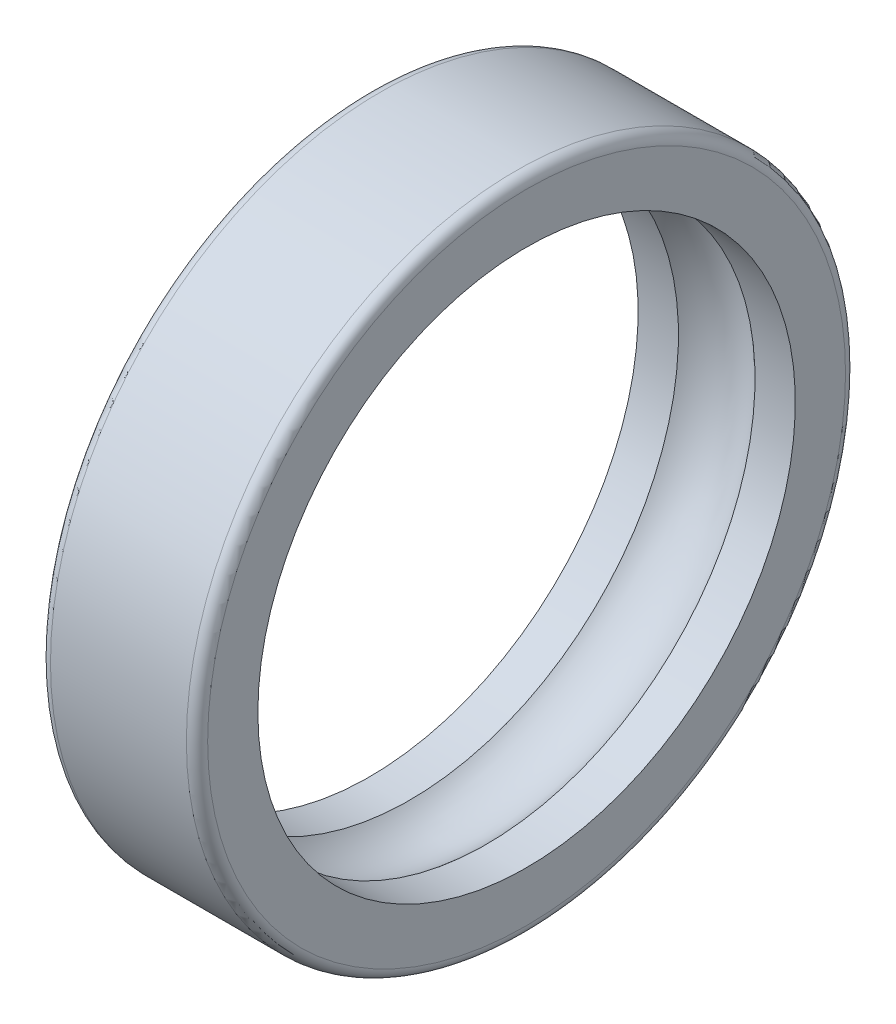
SolidWorks part; units mm, degrees
ref_plane "Front Plane" through (0, 0, 0) normal (0, 0, 1) x (1, 0, 0)
ref_plane "Top Plane" through (0, 0, 0) normal (0, 1, 0) x (1, 0, 0)
ref_plane "Right Plane" through (0, 0, 0) normal (1, 0, 0) x (0, 0, -1)
sketch "Sketch1" plane through (0, 0, 0) normal (0, 1, 0) x (1, 0, 0)
  line L0 (-165.426, 0) -> (533.1166, 0) construction
  line L1 (136.6786, 53) -> (136.6786, 0) construction
  line L2 (152.1786, 53) -> (144.2284, 53)
  line L3 (152.1786, 53) -> (152.1786, 65)
  line L4 (152.1786, 65) -> (121.1786, 65)
  line L5 (121.1786, 53) -> (121.1786, 65)
  line L6 (152.1786, 53) -> (121.1786, 65) construction
  line L7 (152.1786, 65) -> (121.1786, 53) construction
  line L8 (129.1287, 53) -> (121.1786, 53)
  arc A0 (129.1287, 53) -> (144.2284, 53) centre (136.6786, 45) cw
  point P3 (136.6786, 59)
  point P13 (0, 0)
  dimension "D4" = 11
  dimension "D1" = 31
  dimension "D2" = 53
  dimension "D3" = 65
  dimension "D5" = 8
revolve "Revolve1" add sketch "Sketch1" angle 360 about L0
fillet "Fillet2" radius 2.1 2 edges at (152.1786, 0, 65) (121.1786, 0, 65)
